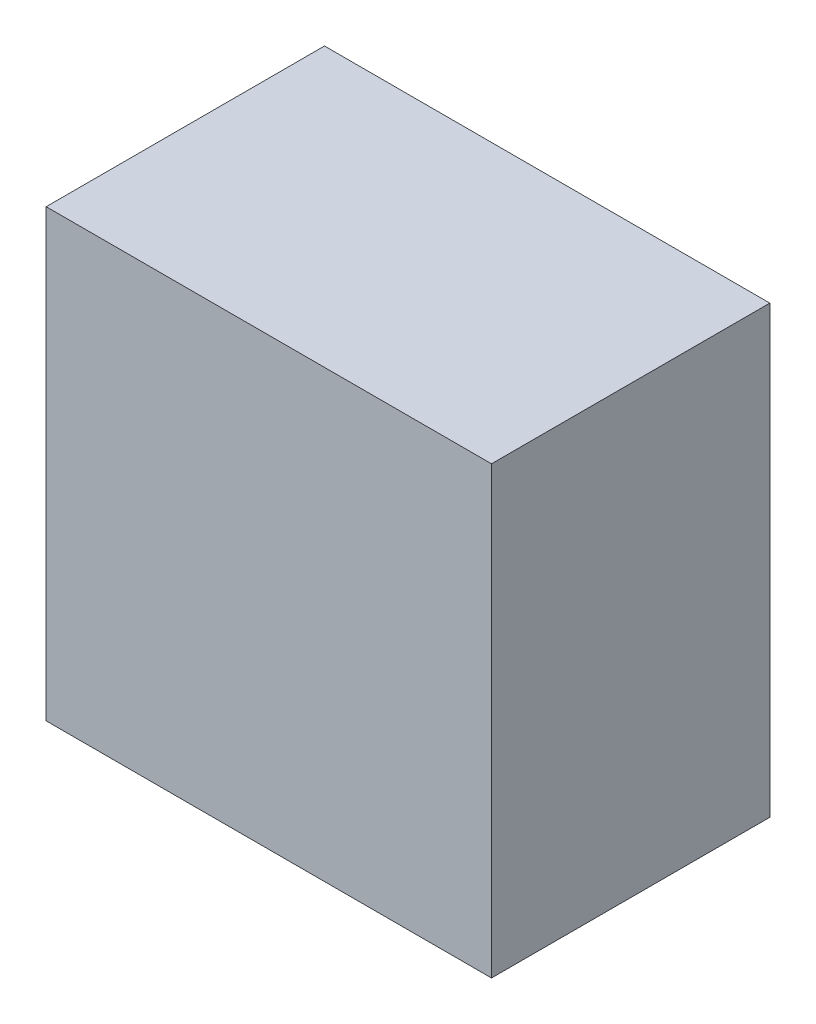
SolidWorks part; units mm, degrees
ref_plane "Front Plane" through (0, 0, 0) normal (0, 0, 1) x (1, 0, 0)
ref_plane "Top Plane" through (0, 0, 0) normal (0, 1, 0) x (1, 0, 0)
ref_plane "Right Plane" through (0, 0, 0) normal (1, 0, 0) x (0, 0, -1)
sketch "Sketch1" plane through (0, 0, 0) normal (0, 0, 1) x (1, 0, 0)
  line L1 (0, 0) -> (8, 0)
  line L2 (0, 0) -> (0, 8)
  line L3 (0, 8) -> (8, 8)
  line L4 (8, 0) -> (8, 8)
  dimension "D1" = 8
extrude "Profile" add sketch "Sketch1" along normal blind 5
equation "\"Profile_Depth\"= 5mm"
equation "\"D1@Profile\" = \"Profile_Depth\""
equation "\"Profile_Sketch_1\"= 8mm"
equation "\"D1@Sketch1\" = \"Profile_Sketch_1\""
equation "\"EnvelopeWidth\"= 8mm"
equation "\"EnvelopeHeight\"= 8mm"
